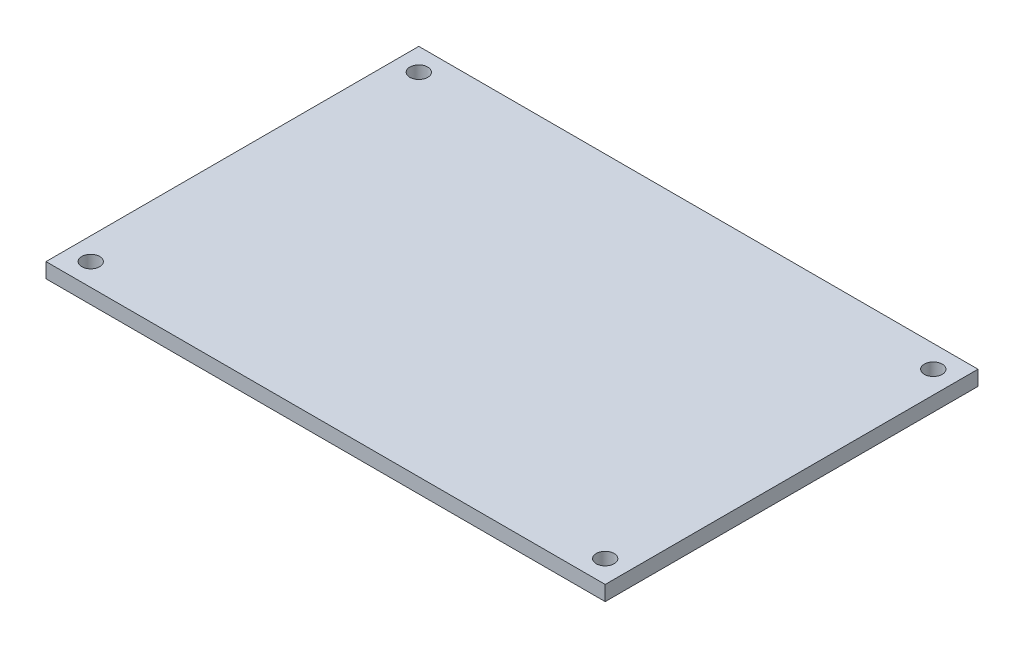
SolidWorks part; units mm, degrees
ref_plane "Front Plane" through (0, 0, 0) normal (0, 0, 1) x (1, 0, 0)
ref_plane "Top Plane" through (0, 0, 0) normal (0, 1, 0) x (1, 0, 0)
ref_plane "Right Plane" through (0, 0, 0) normal (1, 0, 0) x (0, 0, -1)
sketch "Sketch1" plane through (0, 0, 0) normal (0, 1, 0) x (1, 0, 0)
  line L0 (187.5, 0) -> (187.5, -250) construction
  line L1 (0, 0) -> (375, 0)
  line L2 (0, 0) -> (0, -250)
  line L3 (0, -250) -> (375, -250)
  line L4 (375, 0) -> (375, -250)
  line L5 (0, -125) -> (375, -125) construction
  circle A0 centre (360, -15) radius 6
  circle A1 centre (15, -15) radius 6
  circle A2 centre (360, -235) radius 6
  circle A3 centre (15, -235) radius 6
  dimension "D3" = 12
  dimension "D4" = 15
  dimension "D5" = 15
  dimension "D1" = 250
  dimension "D2" = 375
extrude "Boss-Extrude1" add sketch "Sketch1" along normal blind 10
